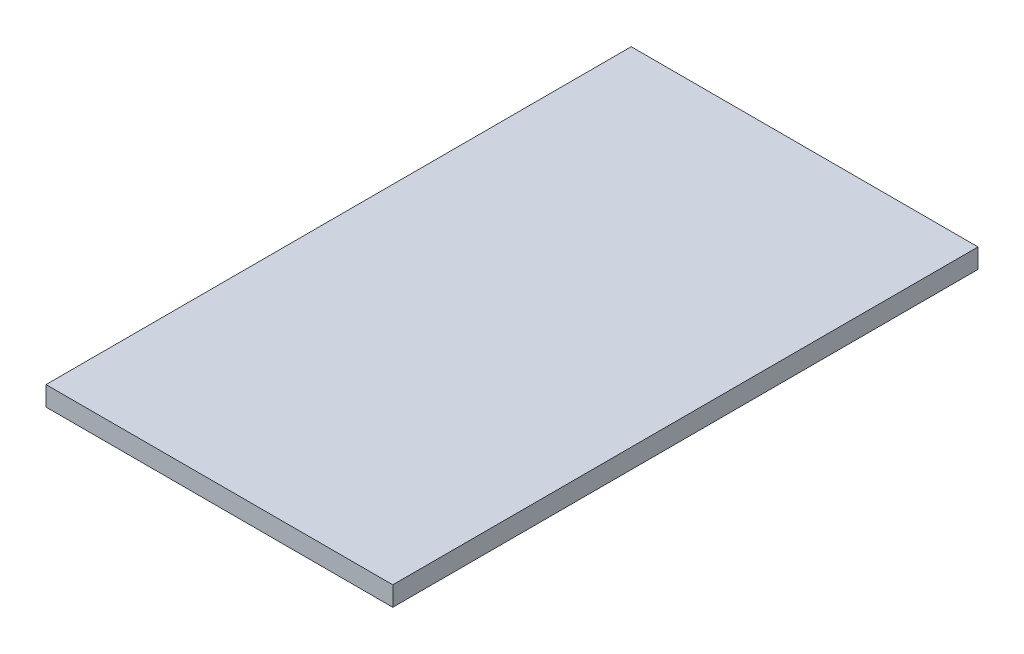
SolidWorks part; units mm, degrees
material "Poplar plywood painted"
ref_plane "Front Plane" through (0, 0, 0) normal (0, 0, 1) x (1, 0, 0)
ref_plane "Top Plane" through (0, 0, 0) normal (0, 1, 0) x (1, 0, 0)
ref_plane "Right Plane" through (0, 0, 0) normal (1, 0, 0) x (0, 0, -1)
sketch "Sketch1" plane through (0, 0, 0) normal (0, 1, 0) x (1, 0, 0)
  line L0 (-80, 135) -> (80, -135) construction
  line L1 (-80, 135) -> (80, 135)
  line L2 (-80, 135) -> (-80, -135)
  line L3 (-80, -135) -> (80, -135)
  line L4 (80, 135) -> (80, -135)
  dimension "D1" = 160
  dimension "D2" = 270
extrude "Boss-Extrude1" add sketch "Sketch1" along normal mid plane 9
